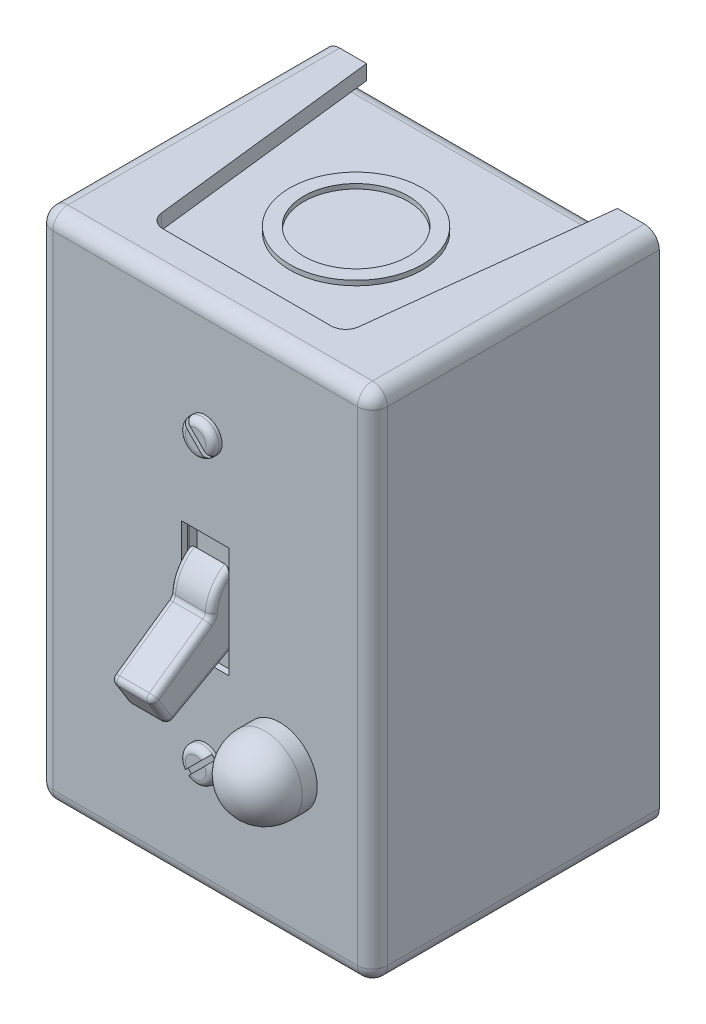
SolidWorks part; units mm, degrees
ref_plane "Front Plane" through (0, 0, 0) normal (0, 0, 1) x (1, 0, 0)
ref_plane "Top Plane" through (0, 0, 0) normal (0, 1, 0) x (1, 0, 0)
ref_plane "Right Plane" through (0, 0, 0) normal (1, 0, 0) x (0, 0, -1)
sketch "Sketch1" plane through (0, 0, 0) normal (0, 0, 1) x (1, 0, 0)
  line L0 (-35.56, -54.61) -> (35.56, 54.61) construction
  line L1 (-35.56, 54.61) -> (35.56, 54.61)
  line L2 (-35.56, 54.61) -> (-35.56, -54.61)
  line L3 (-35.56, -54.61) -> (35.56, -54.61)
  line L4 (35.56, 54.61) -> (35.56, -54.61)
  dimension "D1" = 71.12
  dimension "D2" = 109.22
extrude "Boss-Extrude1" add sketch "Sketch1" along normal blind 60.96
fillet "Fillet1" radius 3.175 8 edges at (0, 54.61, 60.96) (35.56, 0, 60.96) (0, -54.61, 60.96) (-35.56, 0, 60.96) (-35.56, -54.61, 30.48) (35.56, -54.61, 30.48) (-35.56, 54.61, 30.48) (35.56, 54.61, 30.48)
sketch "Sketch2" plane through (0, 54.61, 0) normal (0, 1, 0) x (1, 0, 0)
  line L0 (-20.963, -49.2604) -> (-26.67, 0)
  line L1 (-26.67, 0) -> (26.67, 0)
  line L2 (26.67, 0) -> (20.963, -49.2604)
  line L3 (32.385, 0) -> (-32.385, 0) construction
  line L4 (-35.56, -57.785) -> (-35.56, 0) construction
  line L5 (35.56, 0) -> (35.56, -57.785) construction
  line L6 (35.56, -28.8925) -> (0, -28.8925) construction
  line L7 (-17.8091, -52.07) -> (17.8091, -52.07)
  line L9 (0, -60.96) -> (0, -52.07) construction
  line L11 (32.385, -60.96) -> (-32.385, -60.96) construction
  arc A0 (20.963, -49.2604) -> (17.8091, -52.07) centre (17.8091, -48.895) cw
  circle A1 centre (0, -28.8925) radius 11.1125 construction
  circle A2 centre (0, -28.8925) radius 14.097 construction
  arc A3 (-20.963, -49.2604) -> (-17.8091, -52.07) centre (-17.8091, -48.895) ccw
  point P21 (20.6375, -52.07)
  point P24 (-20.6375, -52.07)
  dimension "D3" = 41.275
  dimension "D4" = 22.225
  dimension "D5" = 28.194
  dimension "D7" = 3.175
  dimension "D1" = 8.89
  dimension "D2" = 8.89
  dimension "D6" = 8.89
extrude "Cut-Extrude1" cut sketch "Sketch2" against normal blind 3.175
sketch "Sketch3" plane through (0, 51.435, 0) normal (0, 1, 0) x (1, 0, 0)
  circle A0 centre (0, -28.8925) radius 11.1125 construction
  circle A1 centre (0, -28.8925) radius 14.097 construction
  circle A2 centre (0, -28.8925) radius 11.1125
  circle A3 centre (0, -28.8925) radius 14.097
extrude "Boss-Extrude5" add sketch "Sketch3" along normal blind 1.016
mirror "Mirror1" about plane through (0, 0, 0) normal (0, 1, 0) of "Boss-Extrude5", "Cut-Extrude1"
sketch "Sketch5" plane through (0, 0, 0) normal (0, 0, -1) x (-1, 0, 0)
  line L12 (-32.385, -51.435) -> (-29.845, -51.435)
  line L13 (32.385, -51.435) -> (32.385, 51.435)
  line L14 (32.385, 51.435) -> (29.845, 51.435)
  line L15 (-32.385, 51.435) -> (-32.385, -51.435)
  line L16 (-32.385, -51.435) -> (32.385, -51.435)
  line L17 (32.385, -51.435) -> (32.385, 51.435)
  line L19 (-32.385, 51.435) -> (-32.385, -51.435)
  line L28 (-29.845, -51.435) -> (-29.845, -48.26)
  line L30 (-29.845, -48.26) -> (29.845, -48.26)
  line L32 (29.845, -48.26) -> (29.845, -51.435)
  line L34 (29.845, -51.435) -> (32.385, -51.435)
  line L36 (29.845, 51.435) -> (29.845, 48.26)
  line L38 (29.845, 48.26) -> (-29.845, 48.26)
  line L40 (-29.845, 48.26) -> (-29.845, 51.435)
  line L42 (-29.845, 51.435) -> (-32.385, 51.435)
  line L43 (32.385, 51.435) -> (-32.385, 51.435)
  dimension "D1" = 3.175
extrude "Cut-Extrude-Thin1" cut sketch "Sketch5" against normal blind 53.975 thin thin type one direction reverse wall 0.508
sketch "Sketch4" plane through (0, 0, 0) normal (0, 0, -1) x (-1, 0, 0)
  line L0 (-20.32, -38.1) -> (20.32, 38.1) construction
  line L1 (-20.32, 38.1) -> (20.32, 38.1) construction
  line L2 (-20.32, 38.1) -> (-20.32, -38.1) construction
  line L3 (-20.32, -38.1) -> (20.32, -38.1) construction
  line L4 (20.32, 38.1) -> (20.32, -38.1) construction
  line L5 (0, 28.9687) -> (0, -28.9687) construction
  circle A0 centre (-20.32, 38.1) radius 3.175
  circle A1 centre (20.32, 38.1) radius 3.175
  circle A3 centre (20.32, -38.1) radius 3.175
  circle A4 centre (0, 28.9687) radius 11.1125
  dimension "D3" = 6.35
  dimension "D4" = 6.35
  dimension "D5" = 22.225
  dimension "D6" = 57.9374
  dimension "D1" = 76.2
  dimension "D2" = 40.64
extrude "Cut-Extrude3" cut sketch "Sketch4" against normal blind 1.016
fillet "Fillet6" radius 3.175 2 edges at (0, 50.927, 0) (0, -50.927, 0)
sketch "Sketch9" plane through (0, 0, 60.96) normal (0, 0, 1) x (1, 0, 0)
  line L0 (-5.08, -11.7475) -> (5.08, 11.7475) construction
  line L1 (-5.08, 11.7475) -> (5.08, 11.7475)
  line L2 (-5.08, 11.7475) -> (-5.08, -11.7475)
  line L4 (-5.08, -11.7475) -> (5.08, -11.7475)
  line L5 (5.08, 11.7475) -> (5.08, -11.7475)
  dimension "D1" = 10.16
  dimension "D2" = 23.495
extrude "Cut-Extrude6" cut sketch "Sketch9" against normal blind 1.27
sketch "Sketch10" plane through (0, 0, 59.69) normal (0, 0, 1) x (1, 0, 0)
  line L0 (-4.7625, -15.0812) -> (4.7625, 15.0812) construction
  line L1 (-4.7625, 15.0812) -> (4.7625, 15.0812)
  line L2 (-4.7625, 15.0812) -> (-4.7625, -15.0812)
  line L3 (-4.7625, -15.0812) -> (4.7625, -15.0813)
  line L4 (4.7625, 15.0812) -> (4.7625, -15.0813)
  dimension "D1" = 9.525
  dimension "D2" = 30.1625
extrude "Cut-Extrude7" cut sketch "Sketch10" against normal blind 1.778
sketch "Sketch11" plane through (0, 0, 0) normal (1, 0, 0) x (0, 0, -1)
  line L0 (-78.486, 3.81) -> (-78.486, -3.81)
  line L1 (-78.486, -3.81) -> (-62.8111, -4.6315)
  line L2 (-78.486, 3.81) -> (-62.8111, 4.6315)
  line L3 (-55.372, 8.763) -> (-55.372, -8.763)
  line L4 (-64.135, 38.8884) -> (-64.135, -38.8884) construction
  line L5 (-60.96, -51.435) -> (-60.96, 51.435) construction
  line L6 (-64.135, 0) -> (-78.486, 0) construction
  arc A0 (-55.372, 8.763) -> (-62.8111, 4.6315) centre (-55.372, 0) ccw
  arc A1 (-62.8111, -4.6315) -> (-55.372, -8.763) centre (-55.372, 0) ccw
  dimension "D1" = 3.175
  dimension "D2" = 7.62
  dimension "D3" = 3
  dimension "D4" = 17.526
  dimension "D5" = 17.526
extrude "Boss-Extrude3" add sketch "Sketch11" along normal mid plane 8.89 separate body
fillet "Fillet5" radius 1.27 17 edges at (4.445, 7.6608, 59.6267) (4.445, 0, 55.372) (4.445, -4.2207, 70.6485) (0, -4.6315, 62.8111) (4.445, -7.6608, 59.6267) (0, -8.763, 55.372) (-4.445, -4.2207, 70.6485) (-4.445, -7.6608, 59.6267) (-4.445, 0, 55.372) (-4.445, 7.6608, 59.6267) (0, 4.6315, 62.8111) (4.445, 4.2207, 70.6485) (-4.445, 4.2207, 70.6485) (0, 3.81, 78.486) (4.445, 0, 78.486) (0, -3.81, 78.486) (-4.445, 0, 78.486)
move or copy body "Body-Move/Copy1" bodies to move or copy 112 copy no rotation origin (0, 0, 55.372) rotation axis (1, 0, 0) rotation angle 32
sketch "Sketch15" plane through (0, 0, 60.96) normal (0, 0, 1) x (1, 0, 0)
  line L0 (0, 30.1625) -> (0, -30.1625) construction
  circle A0 centre (0, 30.1625) radius 3.575
  circle A1 centre (0, -30.1625) radius 3.575
  dimension "D2" = 7.1501
  dimension "D1" = 60.325
extrude "Boss-Extrude6" add sketch "Sketch15" along normal blind 2.032
fillet "Fillet7" radius 1.397 2 edges at (3.5751, -30.1625, 62.992) (3.5751, 30.1625, 62.992)
sketch "Sketch16" plane through (0, 0, 62.992) normal (0, 0, 1) x (1, 0, 0)
  line L0 (-5.178, 35.3405) -> (5.178, 24.9845)
  line L1 (0, 30.1625) -> (-6.7041, 30.1625) construction
  circle A0 centre (0, 30.1625) radius 3.575 construction
  circle A1 centre (0, 30.1625) radius 3.575 construction
  circle A2 centre (0, -30.1625) radius 3.575 construction
  circle A3 centre (0, -30.1625) radius 3.575 construction
  dimension "D1" = 45
extrude "Cut-Extrude-Thin2" cut sketch "Sketch16" against normal blind 1.27 thin thin type mid plane wall 1.016
mirror "Mirror3" about plane through (0, 0, 0) normal (0, 1, 0) of "Cut-Extrude-Thin2"
ref_plane "Plane1" through (15.875, 0, 0) normal (1, 0, 0) x (0, 0, -1)
sketch "Sketch17" plane through (15.875, 0, 0) normal (1, 0, 0) x (0, 0, -1)
  line L0 (-60.96, -22.86) -> (-72.0725, -22.86) construction
  line L1 (-60.96, -51.435) -> (-60.96, 51.435) construction
  line L2 (0, -54.61) -> (-57.785, -54.61) construction
  line L3 (-60.96, -30.7975) -> (-64.135, -30.7975)
  line L4 (-60.96, -30.7975) -> (-60.96, -22.86)
  line L5 (-60.96, -22.86) -> (-72.0725, -22.86)
  arc A0 (-64.135, -30.7975) -> (-72.0725, -22.86) centre (-64.135, -22.86) cw
  dimension "D1" = 31.75
  dimension "D2" = 15.875
  dimension "D3" = 11.1125
revolve "Revolve1" add sketch "Sketch17" angle 360 about L0
